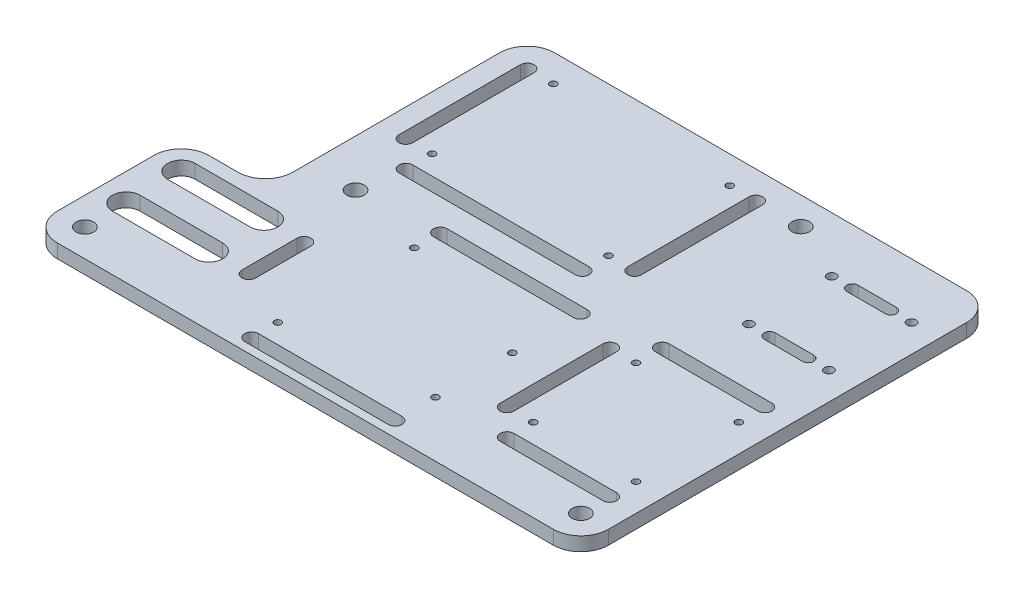
SolidWorks part; units mm, degrees
ref_plane "Front Plane" through (0, 0, 0) normal (0, 0, 1) x (1, 0, 0)
ref_plane "Top Plane" through (0, 0, 0) normal (0, 1, 0) x (1, 0, 0)
ref_plane "Right Plane" through (0, 0, 0) normal (1, 0, 0) x (0, 0, -1)
sketch "Sketch1" plane through (0, 0, 0) normal (0, 1, 0) x (1, 0, 0)
  line L1 (-90, -75) -> (90, -75)
  line L2 (-100, -65) -> (-100, 65)
  line L3 (-90, 75) -> (90, 75)
  line L4 (100, -65) -> (100, 65)
  line L5 (-100, -75) -> (100, 75) construction
  line L6 (-100, 75) -> (100, -75) construction
  arc A0 (90, -75) -> (100, -65) centre (90, -65) ccw
  arc A1 (-90, -75) -> (-100, -65) centre (-90, -65) cw
  arc A2 (-100, 65) -> (-90, 75) centre (-90, 65) cw
  arc A3 (90, 75) -> (100, 65) centre (90, 65) cw
  point P1 (0, 0)
  dimension "D3" = 10
  dimension "D1" = 200
  dimension "D2" = 150
extrude "Boss-Extrude1" add sketch "Sketch1" along normal blind 5 contours L2 A2 L3 A3 L4 A0 L1 A1
hole_wizard "arduino uno holes" positions "Sketch3" profile "Sketch2" tap size "M3x0.5" standard "ANSI Metric" end condition through all
sketch "Sketch3" plane through (0, 5, 0) normal (0, 1, 0) x (1, 0, 0)
  line L0 (-90, -75) -> (90, -75) construction
  line L1 (-100, -65) -> (-100, 65) construction
  point P0 (27.1, -27)
  point P2 (27.1, -54.9)
  point P4 (-23.7, -11.8)
  point P6 (-25, -60)
  dimension "D1" = 27.9
  dimension "D2" = 15.2
  dimension "D3" = 50.8
  dimension "D4" = 1.3
  dimension "D5" = 5.1
  dimension "D6" = 15
  dimension "D7" = 75
sketch "Sketch2" plane through (27.1, 5, 27) normal (1, 0, 0) x (0, 0, 1)
  line L0 (0, 0) -> (0, 5)
  line L1 (0, 5) -> (1.25, 5)
  line L2 (1.25, 5) -> (1.25, 0)
  line L5 (1.25, 0) -> (0, 0)
  line L11 (0, -6.35) -> (0, 107.95) construction
  dimension "Thru Tap Drill Dia." = 2.5
  dimension "Thru Tap Drill Depth" = 5
cosmetic thread "Hole Thread1" parameters "D2"=3
cosmetic thread "Hole Thread2" parameters "D2"=3
cosmetic thread "Hole Thread3" parameters "D2"=3
cosmetic thread "Hole Thread4" parameters "D2"=3
hole_wizard "l298n holes" positions "Sketch16" profile "Sketch17" tap size "M3x0.5" standard "ANSI Metric" end condition through all
sketch "Sketch16" plane through (0, 5, 0) normal (0, 1, 0) x (1, 0, 0)
  line L0 (100, -65) -> (100, 65) construction
  line L1 (-90, -75) -> (90, -75) construction
  point P0 (52.7, -45)
  point P6 (90, -45)
  point P7 (90, -7.7)
  point P8 (52.7, -7.7)
  dimension "D3" = 10
  dimension "D4" = 30
  dimension "D5" = 37.3
  dimension "D6" = 37.3
  dimension "D1" = 2
  dimension "D2" = 2
sketch "Sketch17" plane through (52.7, 5, 45) normal (1, 0, 0) x (0, 0, 1)
  line L0 (0, 0) -> (0, 5)
  line L1 (0, 5) -> (1.25, 5)
  line L2 (1.25, 5) -> (1.25, 0)
  line L5 (1.25, 0) -> (0, 0)
  line L11 (0, -6.35) -> (0, 107.95) construction
  dimension "Thru Tap Drill Dia." = 2.5
  dimension "Thru Tap Drill Depth" = 5
cosmetic thread "Hole Thread25" parameters "D2"=3
cosmetic thread "Hole Thread26" parameters "D2"=3
cosmetic thread "Hole Thread27" parameters "D2"=3
cosmetic thread "Hole Thread28" parameters "D2"=3
hole_wizard "protoboard holes" positions "Sketch20" profile "Sketch21" tap size "M3x0.5" standard "ANSI Metric" end condition through all
sketch "Sketch20" plane through (0, 5, 0) normal (0, 1, 0) x (1, 0, 0)
  line L0 (-90, 75) -> (90, 75) construction
  line L1 (-100, -65) -> (-100, 65) construction
  point P0 (-50, 21)
  point P6 (14, 21)
  point P7 (14, 65)
  point P8 (-50, 65)
  dimension "D3" = 10
  dimension "D4" = 50
  dimension "D5" = 64
  dimension "D6" = 44
  dimension "D1" = 2
  dimension "D2" = 2
sketch "Sketch21" plane through (-50, 5, -21) normal (1, 0, 0) x (0, 0, 1)
  line L0 (0, 0) -> (0, 5)
  line L1 (0, 5) -> (1.25, 5)
  line L2 (1.25, 5) -> (1.25, 0)
  line L5 (1.25, 0) -> (0, 0)
  line L11 (0, -6.35) -> (0, 107.95) construction
  dimension "Thru Tap Drill Dia." = 2.5
  dimension "Thru Tap Drill Depth" = 5
cosmetic thread "Hole Thread37" parameters "D2"=3
cosmetic thread "Hole Thread38" parameters "D2"=3
cosmetic thread "Hole Thread39" parameters "D2"=3
cosmetic thread "Hole Thread40" parameters "D2"=3
hole_wizard "l-bracket holes" positions "Sketch22" profile "Sketch23" tap size "M4x0.7" standard "ANSI Metric" end condition through all
sketch "Sketch22" plane through (0, 5, 0) normal (0, 1, 0) x (1, 0, 0)
  line L0 (-90, 75) -> (90, 75) construction
  line L1 (100, -65) -> (100, 65) construction
  point P12 (61, 55)
  point P19 (90, 55)
  point P20 (90, 25)
  point P21 (61, 25)
  dimension "D1" = 2
  dimension "D2" = 2
  dimension "D3" = 20
  dimension "D4" = 10
sketch "Sketch23" plane through (61, 5, -55) normal (1, 0, 0) x (0, 0, 1)
  line L0 (0, 0) -> (0, 5)
  line L1 (0, 5) -> (1.65, 5)
  line L2 (1.65, 5) -> (1.65, 0)
  line L5 (1.65, 0) -> (0, 0)
  line L11 (0, -6.35) -> (0, 107.95) construction
  dimension "Thru Tap Drill Dia." = 3.3
  dimension "Thru Tap Drill Depth" = 5
cosmetic thread "Hole Thread41" parameters "D2"=4
cosmetic thread "Hole Thread42" parameters "D2"=4
cosmetic thread "Hole Thread43" parameters "D2"=4
cosmetic thread "Hole Thread44" parameters "D2"=4
sketch "Sketch24" plane through (0, 5, 0) normal (0, 1, 0) x (1, 0, 0)
  line L0 (-60, -30) -> (-90, -30) construction
  line L1 (-60, -35) -> (-90, -35)
  line L2 (-60, -25) -> (-90, -25)
  line L3 (-100, -65) -> (-100, 65) construction
  line L4 (-60, -50) -> (-90, -50) construction
  line L5 (-60, -45) -> (-90, -45)
  line L6 (-60, -55) -> (-90, -55)
  line L7 (-90, -75) -> (90, -75) construction
  arc A0 (-60, -35) -> (-60, -25) centre (-60, -30) ccw
  arc A1 (-90, -25) -> (-90, -35) centre (-90, -30) ccw
  arc A2 (-60, -45) -> (-60, -55) centre (-60, -50) cw
  arc A3 (-90, -55) -> (-90, -45) centre (-90, -50) cw
  point P2 (-75, -30)
  point P7 (-95, -30)
  point P8 (-55, -30)
  point P11 (-75, -50)
  dimension "D1" = 10
  dimension "D2" = 40
  dimension "D4" = 20
  dimension "D3" = 5
  dimension "D5" = 10
extrude "power block slots" cut sketch "Sketch24" against normal through all
sketch "Sketch26" plane through (0, 5, 0) normal (0, 1, 0) x (1, 0, 0)
  line L0 (-50, 11.5) -> (14, 11.5) construction
  line L1 (-50, 14) -> (14, 14)
  line L2 (-50, 9) -> (14, 9)
  line L3 (23.5, 65) -> (23.5, 21) construction
  line L4 (26, 65) -> (26, 21)
  line L5 (21, 65) -> (21, 21)
  line L6 (68.5, 55) -> (82.5, 55) construction
  line L7 (68.5, 57) -> (82.5, 57)
  line L8 (68.5, 53) -> (82.5, 53)
  line L9 (68.5, 25) -> (82.5, 25) construction
  line L10 (68.5, 27) -> (82.5, 27)
  line L11 (68.5, 23) -> (82.5, 23)
  line L12 (52.7, 1.8) -> (90, 1.8) construction
  line L13 (52.7, 4.3) -> (90, 4.3)
  line L14 (52.7, -0.7) -> (90, -0.7)
  line L15 (43.2, -7.7) -> (43.2, -45) construction
  line L16 (45.7, -7.7) -> (45.7, -45)
  line L17 (40.7, -7.7) -> (40.7, -45)
  line L18 (-25, -69.5) -> (27.1, -69.5) construction
  line L19 (-25, -67) -> (27.1, -67)
  line L20 (-25, -72) -> (27.1, -72)
  line L21 (-45.5, -30) -> (-45.5, -50) construction
  line L22 (-43, -30) -> (-43, -50)
  line L23 (-48, -30) -> (-48, -50)
  line L24 (-23.7, -2.3) -> (27.1, -2.3) construction
  line L25 (-23.7, 0.2) -> (27.1, 0.2)
  line L26 (-23.7, -4.8) -> (27.1, -4.8)
  line L27 (-59.5, 65) -> (-59.5, 21) construction
  line L28 (-57, 65) -> (-57, 21)
  line L29 (-62, 65) -> (-62, 21)
  line L30 (90, -54.5) -> (52.7, -54.5) construction
  line L31 (90, -57) -> (52.7, -57)
  line L32 (90, -52) -> (52.7, -52)
  arc A0 (-50, 14) -> (-50, 9) centre (-50, 11.5) ccw
  arc A1 (14, 9) -> (14, 14) centre (14, 11.5) ccw
  circle A2 centre (14, 21) radius 1.25 construction
  arc A3 (26, 65) -> (21, 65) centre (23.5, 65) ccw
  arc A4 (21, 21) -> (26, 21) centre (23.5, 21) ccw
  arc A5 (68.5, 57) -> (68.5, 53) centre (68.5, 55) ccw
  arc A6 (82.5, 53) -> (82.5, 57) centre (82.5, 55) ccw
  circle A7 centre (61, 55) radius 1.65 construction
  circle A8 centre (90, 55) radius 1.65 construction
  circle A9 centre (90, 25) radius 1.65 construction
  arc A10 (68.5, 27) -> (68.5, 23) centre (68.5, 25) ccw
  arc A11 (52.7, 4.3) -> (52.7, -0.7) centre (52.7, 1.8) ccw
  arc A12 (90, -0.7) -> (90, 4.3) centre (90, 1.8) ccw
  arc A13 (45.7, -7.7) -> (40.7, -7.7) centre (43.2, -7.7) ccw
  arc A14 (40.7, -45) -> (45.7, -45) centre (43.2, -45) ccw
  circle A15 centre (52.7, -45) radius 1.25 construction
  arc A16 (-25, -67) -> (-25, -72) centre (-25, -69.5) ccw
  arc A17 (27.1, -72) -> (27.1, -67) centre (27.1, -69.5) ccw
  arc A18 (-43, -30) -> (-48, -30) centre (-45.5, -30) ccw
  arc A19 (-48, -50) -> (-43, -50) centre (-45.5, -50) ccw
  circle A20 centre (-25, -60) radius 1.25 construction
  arc A21 (-60, -35) -> (-60, -25) centre (-60, -30) ccw construction
  circle A22 centre (-23.7, -11.8) radius 1.25 construction
  arc A23 (-57, 65) -> (-62, 65) centre (-59.5, 65) ccw
  arc A24 (-62, 21) -> (-57, 21) centre (-59.5, 21) ccw
  circle A25 centre (52.7, -7.7) radius 1.25 construction
  arc A26 (-23.7, 0.2) -> (-23.7, -4.8) centre (-23.7, -2.3) ccw
  arc A27 (27.1, -4.8) -> (27.1, 0.2) centre (27.1, -2.3) ccw
  circle A28 centre (-50, 21) radius 1.25 construction
  arc A29 (90, -57) -> (90, -52) centre (90, -54.5) ccw
  arc A30 (52.7, -52) -> (52.7, -57) centre (52.7, -54.5) ccw
  circle A31 centre (90, -45) radius 1.25 construction
  arc A32 (82.5, 23) -> (82.5, 27) centre (82.5, 25) ccw
  point P2 (-18, 11.5)
  point P11 (23.5, 43)
  point P18 (75.5, 55)
  point P25 (61, 55)
  point P28 (61, 25)
  point P31 (75.5, 25)
  point P36 (71.35, 1.8)
  point P41 (43.2, -26.35)
  point P52 (1.05, -69.5)
  point P59 (-45.5, -40)
  point P72 (1.7, -2.3)
  point P80 (-55, -30)
  point P83 (-59.5, 43)
  point P92 (71.35, -54.5)
  dimension "D1" = 7
  dimension "D2" = 5
  dimension "D3" = 5
  dimension "D4" = 7
  dimension "D9" = 5
  dimension "D10" = 7
  dimension "D11" = 5
  dimension "D12" = 7
  dimension "D15" = 5
  dimension "D16" = 7
  dimension "D17" = 5
  dimension "D18" = 7
  dimension "D13" = 5
  dimension "D14" = 7
  dimension "D19" = 5
  dimension "D20" = 7
  dimension "D21" = 5
  dimension "D22" = 7
  dimension "D5" = 4
  dimension "D6" = 7.5
  dimension "D7" = 7.5
  dimension "D8" = 4
  dimension "D23" = 7.5
  dimension "D24" = 7.5
extrude "cable management slots" cut sketch "Sketch26" against normal through all
sketch "Sketch27" plane through (0, 5, 0) normal (0, 1, 0) x (1, 0, 0)
  line L0 (-69.5, 65) -> (-69.5, -10)
  line L1 (-79.5, -20) -> (-90, -20)
  line L2 (-59.5, 75) -> (-90, 75)
  line L3 (-100, -65) -> (-100, 65) construction
  line L4 (-100, -30) -> (-100, 65)
  circle A0 centre (-59.5, 65) radius 10
  circle A1 centre (-90, -30) radius 10
  arc A2 (-69.5, -10) -> (-79.5, -20) centre (-79.5, -10) cw
  arc A3 (-90, 75) -> (-100, 65) centre (-90, 65) ccw construction
  arc A4 (-90, 75) -> (-100, 65) centre (-90, 65) ccw
  dimension "D1" = 10
extrude "Cut-Extrude3" cut sketch "Sketch27" against normal blind 10 contours L2 A4 L4 A1 L1 A2 L0 A0
hole_wizard "wall-mounting holes" positions "Sketch28" profile "Sketch29" hole size "1/4" standard "ANSI Inch" end condition through all
sketch "Sketch28" plane through (0, 5, 0) normal (0, 1, 0) x (1, 0, 0)
  point P0 (-90, -65)
  point P3 (90, -65)
  point P12 (39.7847, 65)
  point P17 (-52.5, -4.3)
sketch "Sketch29" plane through (-90, 5, 65) normal (1, 0, 0) x (0, 0, 1)
  line L0 (0, 0) -> (0, 5)
  line L1 (0, 5) -> (3.175, 5)
  line L2 (3.175, 5) -> (3.175, 0)
  line L5 (3.175, 0) -> (0, 0)
  line L11 (0, -6.35) -> (0, 107.95) construction
  dimension "Thru Hole Dia." = 6.35
  dimension "Thru Hole Depth" = 5
equation "\"w\"= 200"
equation "\"D1@Sketch1\"=\"w\""
equation "\"h\"= 150"
equation "\"D2@Sketch1\"=\"h\""
equation "\"th\"=5"
equation "\"D1@Boss-Extrude1\"=\"th\""
equation "\"D5@Sketch16\"=\"D6@Sketch16\""
equation "\"slot_w\"= 5"
equation "\"D11@Sketch26\"=\"slot_w\""
equation "\"D9@Sketch26\"=\"slot_w\""
equation "\"D2@Sketch26\"=\"slot_w\""
equation "\"D3@Sketch26\"=\"slot_w\""
equation "\"D15@Sketch26\"=\"slot_w\""
equation "\"D17@Sketch26\"=\"slot_w\""
equation "\"slot_dist\" = 7"
equation "\"D18@Sketch26\"=\"slot_dist\""
equation "\"D12@Sketch26\"=\"slot_dist\""
equation "\"D10@Sketch26\"=\"slot_dist\""
equation "\"D16@Sketch26\"=\"slot_dist\""
equation "\"D4@Sketch26\"=\"slot_dist\""
equation "\"D1@Sketch26\"=\"slot_dist\""
equation "\"D14@Sketch26\"=\"slot_dist\""
equation "\"D13@Sketch26\"=\"slot_w\""
equation "\"D19@Sketch26\"=\"slot_w\""
equation "\"D20@Sketch26\"=\"slot_dist\""
equation "\"D21@Sketch26\"=\"slot_w\""
equation "\"D22@Sketch26\"=\"slot_dist\""
equation "\"D7@Sketch26\"=\"D6@Sketch26\""
equation "\"D8@Sketch26\"=\"D5@Sketch26\""
equation "\"D23@Sketch26\"=\"D6@Sketch26\""
equation "\"D24@Sketch26\"=\"D6@Sketch26\""
